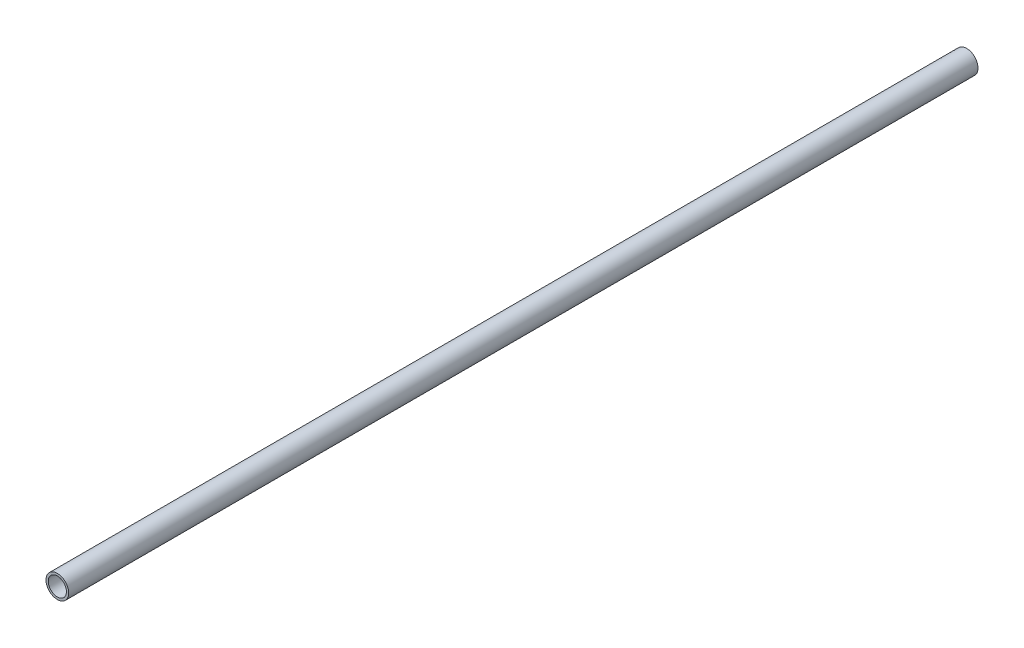
SolidWorks part; units mm, degrees
material "Thornel VCB-20 ｶｰﾎﾞﾝ ｸﾛｽ"
ref_plane "正面" through (0, 0, 0) normal (0, 0, 1) x (1, 0, 0)
ref_plane "平面" through (0, 0, 0) normal (0, 1, 0) x (1, 0, 0)
ref_plane "右側面" through (0, 0, 0) normal (1, 0, 0) x (0, 0, -1)
sketch "ｽｹｯﾁ1" plane through (0, 0, 0) normal (0, 0, 1) x (1, 0, 0)
  circle A0 centre (0, 0) radius 5
  circle A1 centre (0, 0) radius 4
  dimension "D1" = 10
  dimension "D2" = 8
extrude "ﾎﾞｽ - 押し出し1" add sketch "ｽｹｯﾁ1" along normal blind 400
